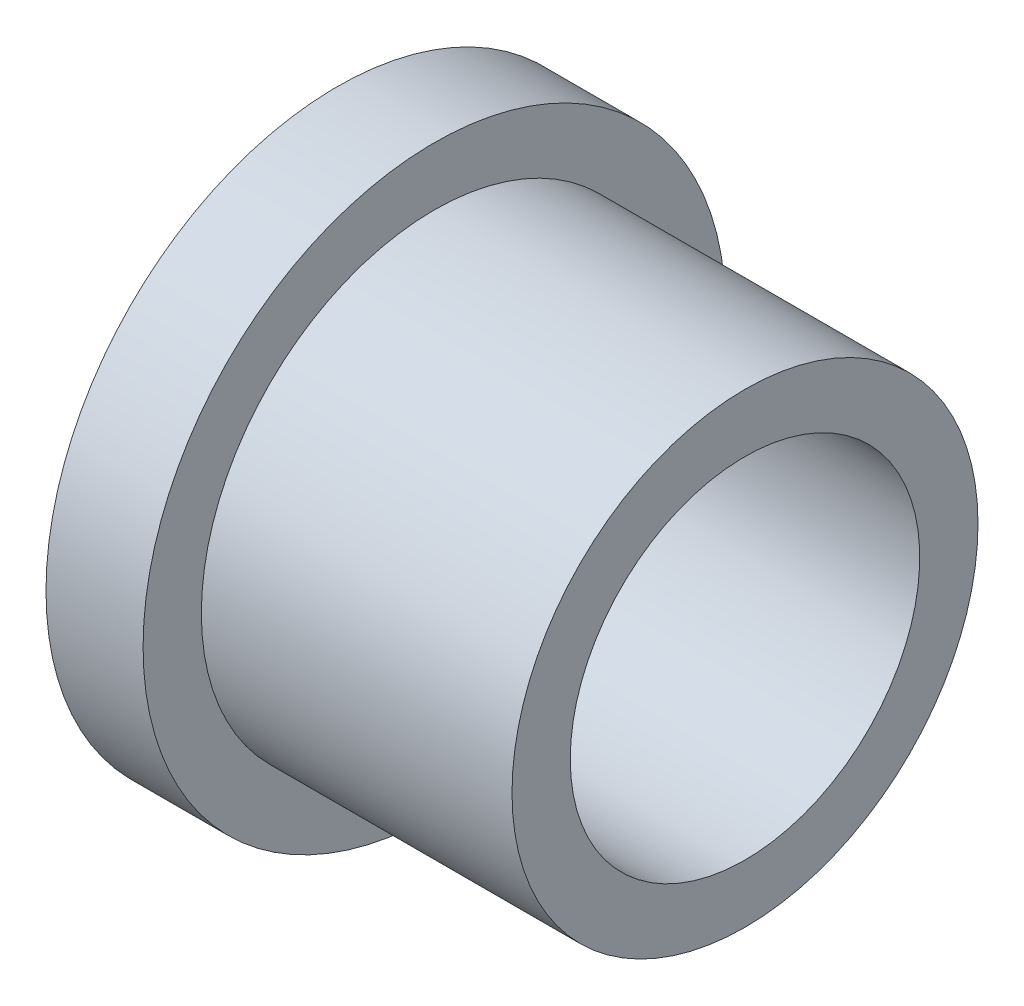
SolidWorks part; units mm, degrees
ref_plane "Front Plane" through (0, 0, 0) normal (0, 0, 1) x (1, 0, 0)
ref_plane "Top Plane" through (0, 0, 0) normal (0, 1, 0) x (1, 0, 0)
ref_plane "Right Plane" through (0, 0, 0) normal (1, 0, 0) x (0, 0, -1)
sketch "Sketch5" plane through (0, 0, 0) normal (0, 0, 1) x (1, 0, 0)
  line L0 (-10.5, 0) -> (10.5, 0)
  line L1 (-10.5, 15) -> (-5.5, 15)
  line L2 (-10.5, 15) -> (-10.5, 0)
  line L4 (10.5, 12) -> (10.5, 0)
  line L10 (-5.5, 15) -> (-5.5, 12)
  line L11 (10.5, 12) -> (-5.5, 12)
  point P0 (0, 0)
revolve "Revolve11" add sketch "Sketch5" angle 360 about L0
shell "Shell2" thickness 3
